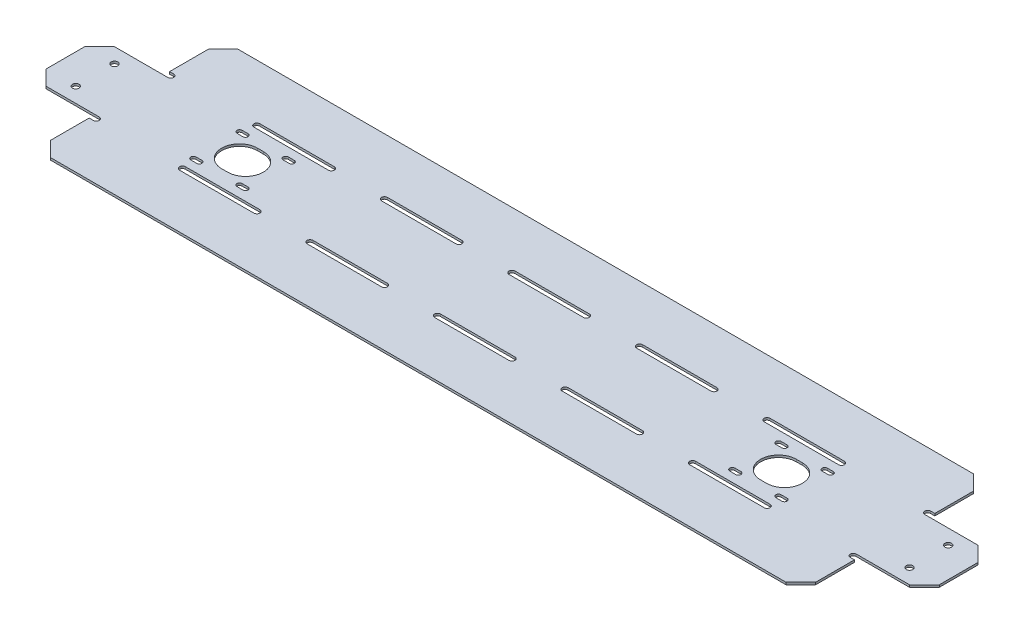
SolidWorks part; units mm, degrees
ref_plane "Front Plane" through (0, 0, 0) normal (0, 0, 1) x (1, 0, 0)
ref_plane "Top Plane" through (0, 0, 0) normal (0, 1, 0) x (1, 0, 0)
ref_plane "Right Plane" through (0, 0, 0) normal (1, 0, 0) x (0, 0, -1)
sketch "Sketch1" plane through (0, 0, 0) normal (0, 1, 0) x (1, 0, 0)
  line L1 (300, 2) -> (300, 48)
  line L2 (43, 48) -> (0, 48)
  line L3 (0, 2) -> (0, 48)
  line L5 (0, 25) -> (15.361, 25) construction
  line L7 (43, -2) -> (43, -38)
  line L8 (43, -38) -> (300, -38)
  line L9 (300, -38) -> (300, -2)
  line L10 (43, 0) -> (128.6667, 0) construction
  line L11 (128.6667, 0) -> (214.3333, 0) construction
  line L12 (214.3333, 0) -> (300, 0) construction
  line L13 (103.6667, 0) -> (153.6667, 0) construction
  line L14 (103.6667, 2) -> (153.6667, 2)
  line L15 (103.6667, -2) -> (153.6667, -2)
  line L16 (189.3333, 0) -> (239.3333, 0) construction
  line L17 (189.3333, 2) -> (239.3333, 2)
  line L18 (189.3333, -2) -> (239.3333, -2)
  line L19 (45.7836, 0) -> (43, 0) construction
  line L20 (45.7836, -2) -> (43, -2)
  line L21 (45.7836, 2) -> (43, 2)
  line L22 (275, 0) -> (300, 0) construction
  line L23 (275, 2) -> (300, 2)
  line L24 (275, -2) -> (300, -2)
  line L25 (300, 88) -> (300, 52)
  line L26 (275, 48) -> (300, 48)
  line L27 (275, 52) -> (300, 52)
  line L28 (189.3333, 50) -> (239.3333, 50) construction
  line L29 (189.3333, 48) -> (239.3333, 48)
  line L30 (189.3333, 52) -> (239.3333, 52)
  line L31 (103.6667, 50) -> (153.6667, 50) construction
  line L32 (103.6667, 48) -> (153.6667, 48)
  line L33 (103.6667, 52) -> (153.6667, 52)
  line L34 (43, 88) -> (300, 88)
  line L35 (45.7836, 52) -> (43, 52)
  line L36 (45.7836, 48) -> (43, 48)
  line L37 (43, 52) -> (43, 88)
  line L39 (43, 2) -> (0, 2)
  arc A0 (103.6667, 2) -> (103.6667, -2) centre (103.6667, 0) ccw
  arc A1 (153.6667, -2) -> (153.6667, 2) centre (153.6667, 0) ccw
  arc A2 (189.3333, 2) -> (189.3333, -2) centre (189.3333, 0) ccw
  arc A3 (239.3333, -2) -> (239.3333, 2) centre (239.3333, 0) ccw
  arc A4 (45.7836, -2) -> (45.7836, 2) centre (45.7836, 0) ccw
  arc A6 (275, 2) -> (275, -2) centre (275, 0) ccw
  arc A7 (275, 48) -> (275, 52) centre (275, 50) cw
  arc A8 (189.3333, 48) -> (189.3333, 52) centre (189.3333, 50) cw
  arc A9 (239.3333, 52) -> (239.3333, 48) centre (239.3333, 50) cw
  arc A10 (103.6667, 48) -> (103.6667, 52) centre (103.6667, 50) cw
  arc A11 (153.6667, 52) -> (153.6667, 48) centre (153.6667, 50) cw
  arc A12 (45.7836, 52) -> (45.7836, 48) centre (45.7836, 50) cw
  point P15 (128.6667, 0)
  point P21 (214.3333, 0)
  point P28 (55.5, 0)
  point P34 (287.5, 0)
  point P49 (214.3333, 50)
  point P56 (128.6667, 50)
  dimension "D10" = 2
  dimension "D5" = 38
  dimension "D7" = 257
  dimension "D9" = 50
  dimension "D12" = 25
extrude "Boss-Extrude1" add sketch "Sketch1" along normal blind 1.5
sketch "Sketch3" plane through (0, 1.5, 0) normal (0, 1, 0) x (1, 0, 0)
  line L0 (40, 50) -> (40, 0) construction
  line L1 (0, 0) -> (41, 0) construction
  line L2 (40, 25) -> (300, 25) construction
  line L3 (300, -38) -> (300, -2) construction
  line L4 (117, 25) -> (121, 25) construction
  line L5 (117, 37) -> (121, 37)
  line L6 (117, 13) -> (121, 13)
  line L7 (119, 25) -> (99.0568, 44.9432) construction
  line L8 (119, 25) -> (138.4592, 5.5408) construction
  line L9 (119, 25) -> (100.845, 6.845) construction
  line L10 (119, 25) -> (134.1665, 40.1665) construction
  line L11 (103.5, 40.5) -> (134.5, 40.5) construction
  line L12 (134.5, 40.5) -> (134.5, 9.5) construction
  line L13 (134.5, 9.5) -> (103.5, 9.5) construction
  line L14 (103.5, 9.5) -> (103.5, 40.5) construction
  line L15 (101.5, 9.5) -> (105.5, 9.5) construction
  line L16 (101.5, 11.25) -> (105.5, 11.25)
  line L17 (101.5, 7.75) -> (105.5, 7.75)
  line L18 (136.5, 9.5) -> (132.5, 9.5) construction
  line L19 (136.5, 7.75) -> (132.5, 7.75)
  line L20 (136.5, 11.25) -> (132.5, 11.25)
  line L21 (132.5, 40.5) -> (136.5, 40.5) construction
  line L22 (132.5, 42.25) -> (136.5, 42.25)
  line L23 (132.5, 38.75) -> (136.5, 38.75)
  line L24 (105.5, 40.5) -> (101.5, 40.5) construction
  line L25 (105.5, 38.75) -> (101.5, 38.75)
  line L26 (105.5, 42.25) -> (101.5, 42.25)
  arc A0 (117, 37) -> (117, 13) centre (117, 25) ccw
  arc A1 (121, 13) -> (121, 37) centre (121, 25) ccw
  arc A2 (101.5, 11.25) -> (101.5, 7.75) centre (101.5, 9.5) ccw
  arc A3 (105.5, 7.75) -> (105.5, 11.25) centre (105.5, 9.5) ccw
  arc A4 (136.5, 7.75) -> (136.5, 11.25) centre (136.5, 9.5) ccw
  arc A5 (132.5, 11.25) -> (132.5, 7.75) centre (132.5, 9.5) ccw
  arc A6 (132.5, 42.25) -> (132.5, 38.75) centre (132.5, 40.5) ccw
  arc A7 (136.5, 38.75) -> (136.5, 42.25) centre (136.5, 40.5) ccw
  arc A8 (105.5, 38.75) -> (105.5, 42.25) centre (105.5, 40.5) ccw
  arc A9 (101.5, 42.25) -> (101.5, 38.75) centre (101.5, 40.5) ccw
  point P11 (119, 25)
  point P26 (103.5, 9.5)
  point P33 (134.5, 9.5)
  point P40 (134.5, 40.5)
  point P47 (103.5, 40.5)
  dimension "D3" = 12
  dimension "D4" = 1.75
  dimension "D1" = 79
  dimension "D2" = 4
  dimension "D5" = 31
extrude "Cut-Extrude2" cut sketch "Sketch3" against normal blind 3
ref_plane "Plane1" through (300, 0, 0) normal (1, 0, 0) x (0, 0, -1)
mirror "Mirror3" about plane through (300, 0, 0) normal (1, 0, 0) of bodies 103
sketch "Sketch4" plane through (0, 1.5, 0) normal (0, 1, 0) x (1, 0, 0)
  line L0 (20, 48) -> (20, 2) construction
  line L1 (45.7836, 48) -> (0, 48) construction
  line L2 (0, 2) -> (45.7836, 2) construction
  line L3 (0, 48) -> (0, 2) construction
  circle A0 centre (20, 38) radius 2.25
  circle A1 centre (20, 12) radius 2.25
  dimension "D2" = 4.5
  dimension "D3" = 10
  dimension "D1" = 20
  dimension "D4" = 10
extrude "Cut-Extrude3" cut sketch "Sketch4" against normal blind 10
mirror "Mirror4" about plane through (300, 0, 0) normal (1, 0, 0) of "Cut-Extrude3"
chamfer "Chamfer3" distance 10 angle 45 4 edges at (43, 0.75, 38) (0, 0.75, -2) (0, 0.75, -48) (43, 0.75, -88)
chamfer "Chamfer4" distance 10 angle 45 4 edges at (557, 0.75, 38) (600, 0.75, -2) (600, 0.75, -48) (557, 0.75, -88)
